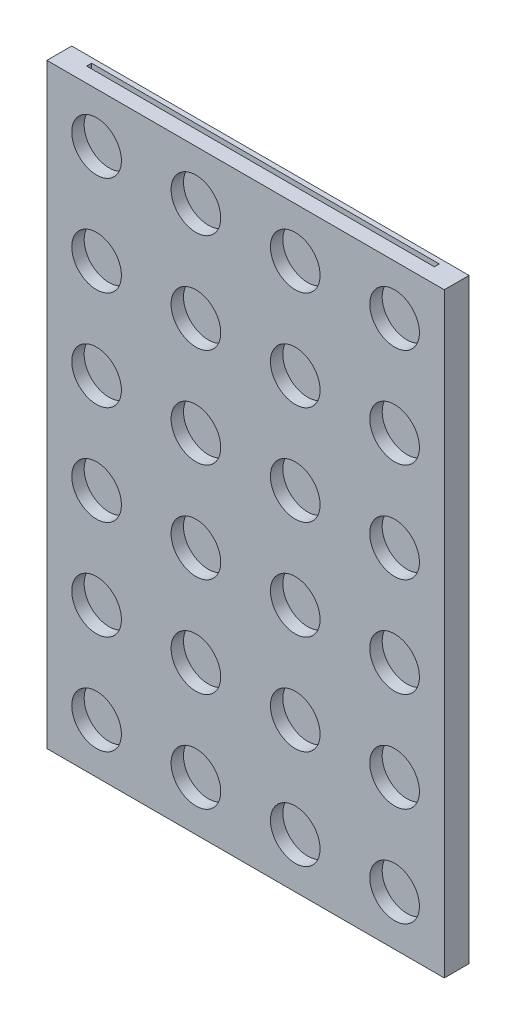
SolidWorks part; units mm, degrees
ref_plane "Front Plane" through (0, 0, 0) normal (0, 0, 1) x (1, 0, 0)
ref_plane "Top Plane" through (0, 0, 0) normal (0, 1, 0) x (1, 0, 0)
ref_plane "Right Plane" through (0, 0, 0) normal (1, 0, 0) x (0, 0, -1)
sketch "Sketch1" plane through (0, 0, 0) normal (0, 0, 1) x (1, 0, 0)
  line L1 (0, 0) -> (101.6, 0)
  line L2 (0, 0) -> (0, 152.4)
  line L3 (0, 152.4) -> (101.6, 152.4)
  line L4 (101.6, 0) -> (101.6, 152.4)
  dimension "D1" = 152.4
  dimension "D2" = 101.6
extrude "Boss-Extrude1" add sketch "Sketch1" along normal blind 6.35
sketch "Sketch3" plane through (0, 0, 6.35) normal (0, 0, 1) x (1, 0, 0)
  line L0 (0, 152.4) -> (0, 0) construction
  line L1 (101.6, 152.4) -> (0, 152.4) construction
  line L2 (0, 0) -> (101.6, 0) construction
  line L3 (25.4, 152.4) -> (25.4, 0)
  line L5 (12.7, 152.4) -> (12.7, 0)
  line L6 (38.1, 152.4) -> (38.1, 0)
  line L7 (50.8, 152.4) -> (50.8, 0)
  line L8 (63.5, 152.4) -> (63.5, 0)
  line L9 (76.2, 152.4) -> (76.2, 0)
  line L10 (88.9, 152.4) -> (88.9, 0)
  line L11 (0, 12.7) -> (101.6, 12.7)
  line L12 (101.6, 0) -> (101.6, 152.4) construction
  line L13 (0, 25.4) -> (101.6, 25.4)
  line L14 (0, 38.1) -> (101.6, 38.1)
  line L15 (0, 50.8) -> (101.6, 50.8)
  line L16 (0, 63.5) -> (101.6, 63.5)
  line L17 (0, 63.6141) -> (101.6, 63.6141)
  line L18 (0, 76.2) -> (101.6, 76.2)
  line L19 (0, 88.9) -> (101.6, 88.9)
  line L20 (0, 101.6) -> (101.6, 101.6)
  line L21 (0, 114.3) -> (101.6, 114.3)
  line L22 (0, 127) -> (101.6, 127)
  line L23 (0, 139.7) -> (101.6, 139.7)
  circle A0 centre (12.7, 139.7) radius 6.35
  circle A2 centre (38.1, 139.7) radius 6.35
  circle A4 centre (63.5, 139.7) radius 6.35
  circle A6 centre (88.9, 139.7) radius 6.35
  circle A7 centre (88.9, 114.3) radius 6.35
  circle A8 centre (63.5, 114.3) radius 6.35
  circle A9 centre (38.1, 114.3) radius 6.35
  circle A10 centre (12.7, 114.3) radius 6.35
  circle A11 centre (88.9, 88.9) radius 6.35
  circle A12 centre (63.5, 88.9) radius 6.35
  circle A13 centre (38.1, 88.9) radius 6.35
  circle A14 centre (12.7, 88.9) radius 6.35
  circle A15 centre (88.9, 63.5) radius 6.35
  circle A16 centre (63.5, 63.5) radius 6.35
  circle A17 centre (38.1, 63.5) radius 6.35
  circle A18 centre (12.7, 63.5) radius 6.35
  circle A19 centre (88.9, 38.1) radius 6.35
  circle A20 centre (63.5, 38.1) radius 6.35
  circle A21 centre (38.1, 38.1) radius 6.35
  circle A22 centre (12.7, 38.1) radius 6.35
  circle A23 centre (88.9, 12.7) radius 6.35
  circle A24 centre (63.5, 12.7) radius 6.35
  circle A25 centre (38.1, 12.7) radius 6.35
  circle A26 centre (12.7, 12.7) radius 6.35
  point P10 (0, 0)
  dimension "D1" = 12.7
  dimension "D2" = 12.7
  dimension "D3" = 12.7
  dimension "D4" = 12.7
  dimension "D5" = 12.7
  dimension "D6" = 12.7
  dimension "D7" = 12.7
  dimension "D8" = 12.7
  dimension "D9" = 12.7
  dimension "D10" = 12.7
  dimension "D11" = 12.7
  dimension "D12" = 12.7
  dimension "D13" = 12.7
  dimension "D14" = 12.7
  dimension "D15" = 12.7
  dimension "D16" = 12.7
  dimension "D17" = 12.7
  dimension "D18" = 12.7
extrude "Cut-Extrude2" cut sketch "Sketch3" against normal blind 3.175 contours A0 | A2 | A4 | A6 | A7 | A8 | A9 | A10 | A14 | A13 | A12 | A11 | A18 | A17 | A16 | A15 | A22 | A21 | A20 | A19 | A26 | A25 | A24 | A23
sketch "Sketch4" plane through (0, 0, 0) normal (0, 0, -1) x (-1, 0, 0)
  line L0 (-95.25, 146.05) -> (-95.25, 6.35)
  line L1 (-95.25, 6.35) -> (-6.35, 6.35)
  line L2 (-6.35, 6.35) -> (-6.35, 146.05)
  line L3 (-6.35, 146.05) -> (-95.25, 146.05)
  line L4 (-101.6, 0) -> (-101.6, 152.4) construction
  line L5 (0, 0) -> (-101.6, 0) construction
  line L6 (0, 152.4) -> (0, 0) construction
  line L7 (-101.6, 152.4) -> (0, 152.4) construction
  dimension "D1" = 6.35
  dimension "D2" = 6.35
  dimension "D3" = 6.35
  dimension "D4" = 6.35
extrude "Cut-Extrude3" cut sketch "Sketch4" against normal blind 2.54
sketch "Sketch5" plane through (0, 152.4, 0) normal (0, 1, 0) x (1, 0, 0)
  line L0 (6.35, -1.27) -> (95.25, -1.27)
  line L1 (95.25, -1.27) -> (95.25, -2.54)
  line L2 (95.25, -2.54) -> (6.35, -2.54)
  line L3 (6.35, -2.54) -> (6.35, -1.27)
  line L4 (0, -6.35) -> (0, 0) construction
  line L5 (101.6, -6.35) -> (101.6, 0) construction
  line L6 (101.6, 0) -> (0, 0) construction
  dimension "D1" = 6.35
  dimension "D2" = 6.35
  dimension "D3" = 1.27
  dimension "D4" = 1.27
extrude "Cut-Extrude4" cut sketch "Sketch5" against normal up to next
